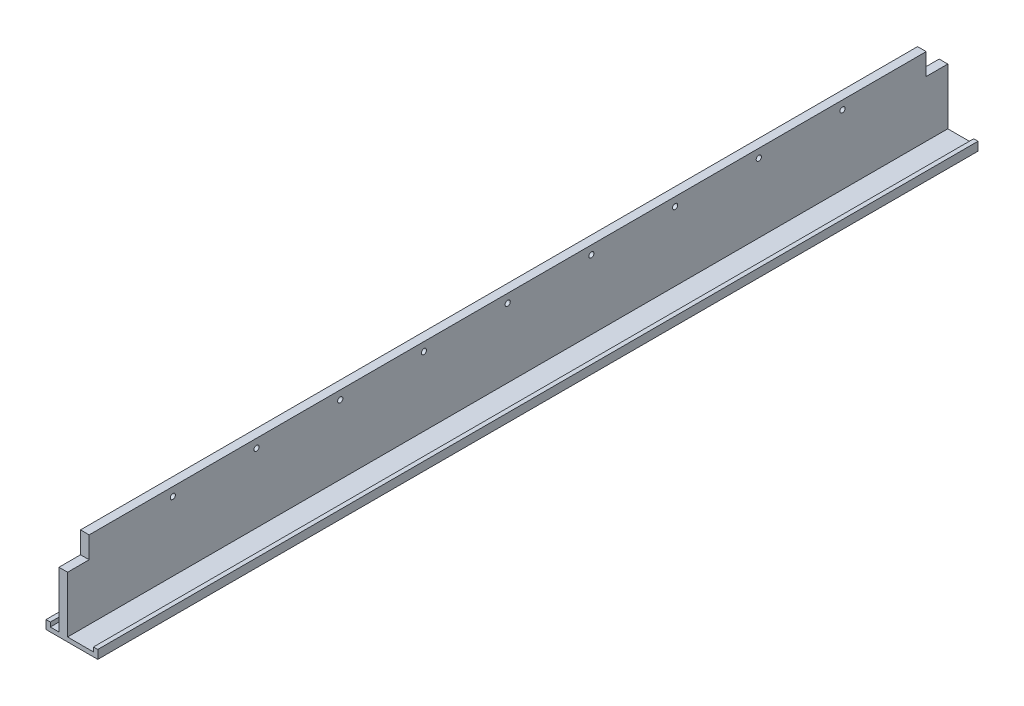
SolidWorks part; units mm, degrees
material "Acrylic (Medium-high impact)"
ref_plane "Front Plane" through (0, 0, 0) normal (0, 0, 1) x (1, 0, 0)
ref_plane "Top Plane" through (0, 0, 0) normal (0, 1, 0) x (1, 0, 0)
ref_plane "Right Plane" through (0, 0, 0) normal (1, 0, 0) x (0, 0, -1)
sketch "Sketch1" plane through (0, 0, 0) normal (0, 0, 1) x (1, 0, 0)
  line L0 (0, 10) -> (0, 0)
  line L1 (0, 0) -> (60, 0)
  line L2 (60, 0) -> (60, 10)
  line L3 (60, 10) -> (55, 10)
  line L4 (55, 10) -> (55, 5)
  line L5 (55, 5) -> (25, 5)
  line L6 (25, 5) -> (25, 95)
  line L7 (25, 95) -> (15, 95)
  line L8 (15, 95) -> (15, 5)
  line L9 (15, 5) -> (5, 5)
  line L10 (5, 5) -> (5, 10)
  line L11 (5, 10) -> (0, 10)
  dimension "D1" = 10
  dimension "D2" = 10
  dimension "D3" = 5
  dimension "D4" = 5
  dimension "D5" = 5
  dimension "D6" = 10
  dimension "D7" = 60
  dimension "D8" = 95
  dimension "D9" = 5
extrude "Boss-Extrude1" add sketch "Sketch1" along normal blind 1020
sketch "Sketch2" plane through (25, 0, 0) normal (1, 0, 0) x (0, 0, -1)
  line L0 (-1052.1126, 85) -> (45.5589, 85) construction
  line L1 (-1020, 95) -> (-995, 95)
  line L2 (-1020, 95) -> (-1020, 70)
  line L3 (-1020, 70) -> (-995, 70)
  line L4 (-995, 95) -> (-995, 70)
  line L5 (0, 95) -> (-25, 95)
  line L6 (0, 95) -> (0, 70)
  line L7 (0, 70) -> (-25, 70)
  line L8 (-25, 95) -> (-25, 70)
  line L9 (-1020, 95) -> (0, 95) construction
  dimension "D1" = 25
  dimension "D2" = 25
  dimension "D3" = 25
  dimension "D4" = 25
  dimension "D5" = 10
extrude "Cut-Extrude1" cut sketch "Sketch2" against normal blind 10
sketch "Sketch3" plane through (25, 0, 0) normal (1, 0, 0) x (0, 0, -1)
  line L0 (-995, 70) -> (-995, 95) construction
  line L1 (-995, 95) -> (-25, 95) construction
  circle A0 centre (-898, 85) radius 3
  dimension "D3" = 6
  dimension "D1" = 97
  dimension "D2" = 10
extrude "Cut-Extrude2" cut sketch "Sketch3" against normal blind 10
pattern_linear "LPattern1" count 9 spacing 97 along (0, 0, -1) of "Cut-Extrude2"
